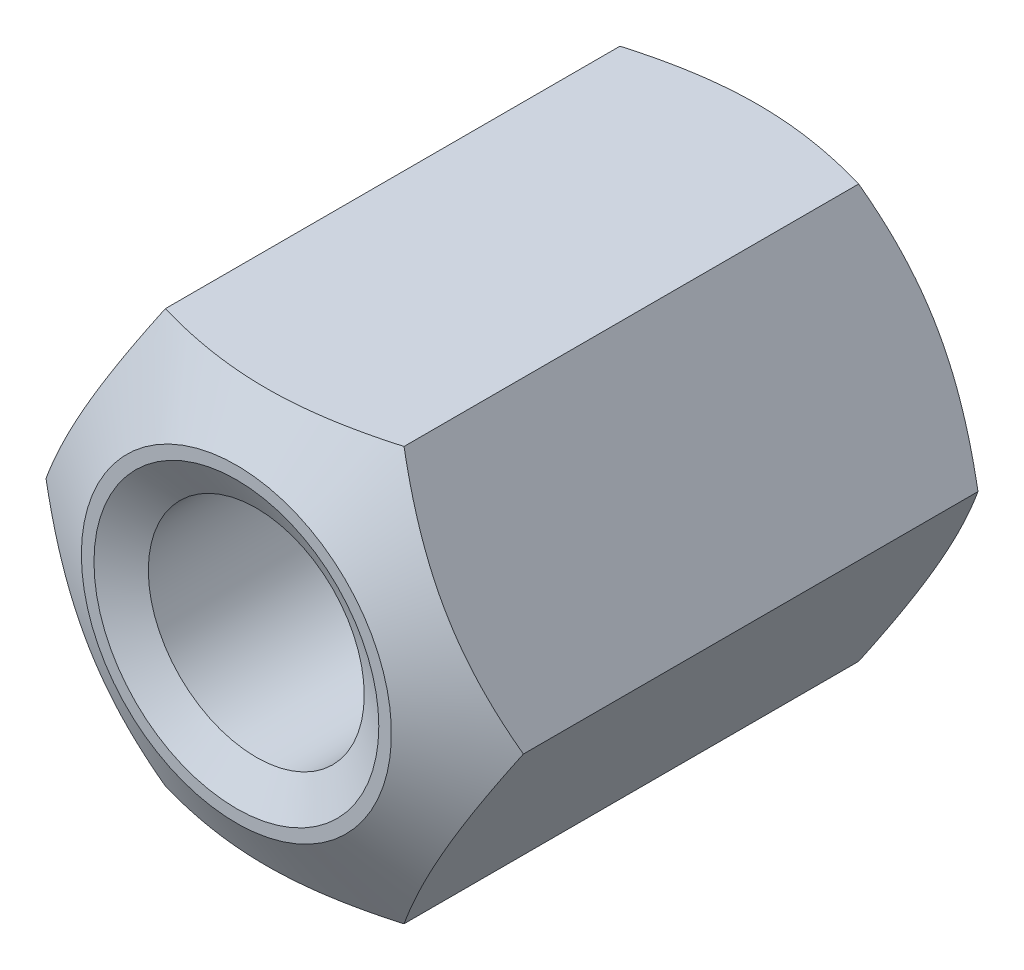
SolidWorks part; units mm, degrees
ref_plane "Front" through (0, 0, 0) normal (0, 0, 1) x (1, 0, 0)
ref_plane "Top" through (0, 0, 0) normal (0, 1, 0) x (1, 0, 0)
ref_plane "Right" through (0, 0, 0) normal (1, 0, 0) x (0, 0, -1)
sketch "Sketch1" plane through (0, 0, 0) normal (0, 0, 1) x (1, 0, 0)
  line L1 (0.866, -1.5) -> (1.7321, 0)
  line L2 (1.7321, 0) -> (0.866, 1.5)
  line L3 (0.866, 1.5) -> (-0.866, 1.5)
  line L4 (-0.866, 1.5) -> (-1.7321, 0)
  line L5 (-1.7321, 0) -> (-0.866, -1.5)
  line L6 (-0.866, -1.5) -> (0.866, -1.5)
  circle A0 centre (0, 0) radius 1.5 construction
  circle A1 centre (0, 0) radius 0.7835
  dimension "D" = 1.567
  dimension "s" = 3
extrude "BaseNut" add sketch "Sketch1" against normal blind 4
cosmetic thread "ThreadCosmetic1" [suppressed] parameters "D"=2
sketch "Sketch2" plane through (0, 0, 0) normal (0, 1, 0) x (1, 0, 0)
  line L0 (-1.7321, 4) -> (-1.125, 4)
  line L2 (-1.125, 4) -> (-1.7321, 3.6495)
  line L3 (-1.7321, 3.6495) -> (-1.7321, 4)
  line L4 (0, 9.8171) -> (0, -9.8171) construction
  line L6 (-9.7712, 2) -> (9.8853, 2) construction
  line L7 (-1.7321, 0.3505) -> (-1.7321, 0)
  line L8 (-1.125, 0) -> (-1.7321, 0.3505)
  line L9 (-1.7321, 0) -> (-1.125, 0)
  dimension "dw" = 2.25
  dimension "D1" = 30
  dimension "D2" = 2
revolve "Double-Chamfer" cut sketch "Sketch2" angle 360 about L4
chamfer "EndChamfer" distance 0.25 angle 30 2 edges at (0.7835, 0, -4) (0.7835, 0, 0)
sketch "Sketch3" plane through (0, 0, 0) normal (0, 1, 0) x (1, 0, 0)
  line L0 (-0.971, 3.75) -> (-0.7835, 3.6417)
  line L1 (-0.7835, 3.6417) -> (-0.567, 3.6417)
  line L2 (-0.567, 3.6417) -> (-0.567, 3.8582)
  line L3 (-0.567, 3.8582) -> (-0.7835, 3.8582)
  line L4 (-0.7835, 3.8582) -> (-0.971, 3.75)
  line L5 (0, 5.5171) -> (0, 12.3415) construction
  dimension "D1" = 0.2165
  dimension "D2" = 1.567
revolve "Cut-Revolve10" [suppressed] cut sketch "Sketch3" angle 360 about L5
pattern_linear "LPattern10" [suppressed] count 14 spacing 0.2598 along (0, 0, -1)
equation "\"dw@Sketch2\" = \"s@Sketch1\"-0.75"
equation "\"D1@EndChamfer\" = \"m@BaseNut\" / 16"
equation "\"D2@Sketch2\" = \"m@BaseNut\" / 2"
equation "\"D2@Sketch3\"=\"D@Sketch1\""
equation "\"D1@Sketch3\" =  ( \"D@ThreadCosmetic1\" - \"D@Sketch1\" )  / 2"
equation "\"D3@LPattern10\"=\"D1@Sketch3\" * 1.2"
equation "\"D1@LPattern10\" = \"m@BaseNut\" / \"D3@LPattern10\"-1"
